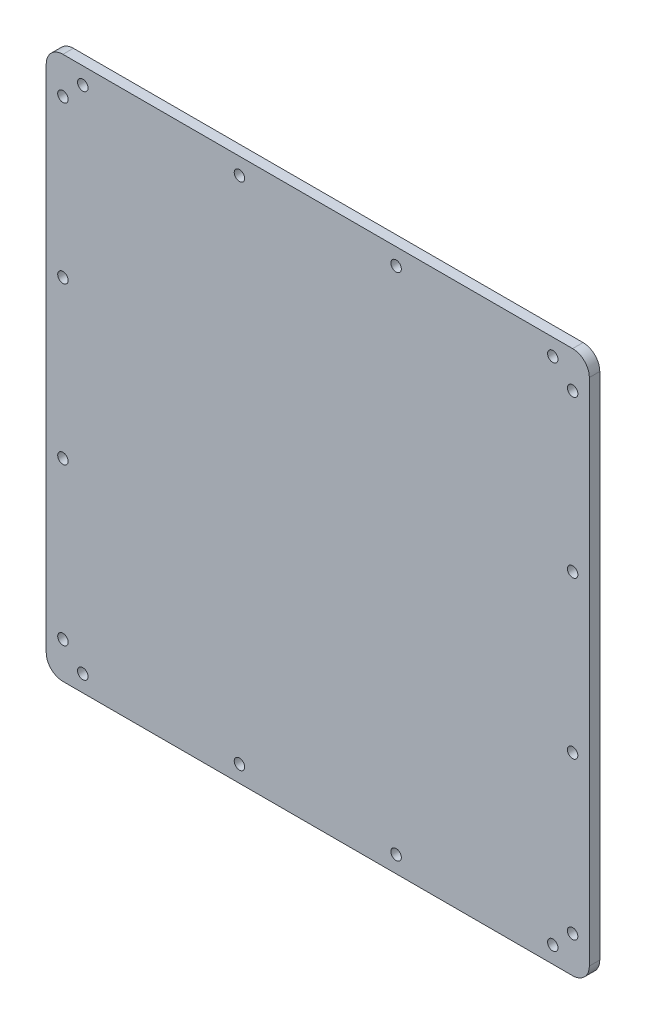
SolidWorks part; units mm, degrees
ref_plane "前视基准面" through (0, 0, 0) normal (0, 0, 1) x (1, 0, 0)
ref_plane "上视基准面" through (0, 0, 0) normal (0, 1, 0) x (1, 0, 0)
ref_plane "右视基准面" through (0, 0, 0) normal (1, 0, 0) x (0, 0, -1)
sketch "草图1" plane through (0, 0, 0) normal (0, 0, 1) x (1, 0, 0)
  line L0 (92.5, 8) -> (167.5, 8) construction
  line L1 (8, 260) -> (252, 260)
  line L2 (0, 252) -> (0, 8)
  line L3 (8, 0) -> (252, 0)
  line L4 (260, 252) -> (260, 8)
  line L5 (130, 318.6966) -> (130, -302.6966) construction
  line L6 (252, 167.5) -> (252, 92.5) construction
  line L7 (-174.8199, 130) -> (374.3981, 130) construction
  arc A0 (8, 0) -> (0, 8) centre (8, 8) cw
  arc A1 (252, 0) -> (260, 8) centre (252, 8) ccw
  arc A2 (260, 252) -> (252, 260) centre (252, 252) ccw
  arc A3 (0, 252) -> (8, 260) centre (8, 252) cw
  circle A4 centre (17.5, 8) radius 2.5
  circle A5 centre (92.5, 8) radius 2.5
  circle A6 centre (167.5, 8) radius 2.5
  circle A7 centre (242.5, 8) radius 2.5
  circle A8 centre (252, 242.5) radius 2.5
  circle A9 centre (252, 167.5) radius 2.5
  circle A10 centre (252, 92.5) radius 2.5
  circle A11 centre (252, 17.5) radius 2.5
  circle A12 centre (242.5, 252) radius 2.5
  circle A13 centre (167.5, 252) radius 2.5
  circle A14 centre (92.5, 252) radius 2.5
  circle A15 centre (17.5, 252) radius 2.5
  circle A16 centre (8, 17.5) radius 2.5
  circle A17 centre (8, 92.5) radius 2.5
  circle A18 centre (8, 167.5) radius 2.5
  circle A19 centre (8, 242.5) radius 2.5
  point P8 (0, 0)
  point P13 (260, 260)
  point P16 (0, 260)
  point P26 (130, 8)
  point P27 (130, 0)
  point P38 (260, 130)
  point P39 (252, 130)
  point P40 (132.5, 318.6966)
  point P41 (-174.8199, 132.5)
  point P42 (374.3981, 132.5)
  dimension "D3" = 8
  dimension "D4" = 5
  dimension "D5" = 4
  dimension "D6" = 5
  dimension "D1" = 260
  dimension "D2" = 260
  dimension "D8" = 75
  dimension "D9" = 75
  dimension "D10" = 8
  dimension "D11" = 8
  dimension "D7" = 4
extrude "凸台-拉伸4" add sketch "草图1" along normal blind 5
